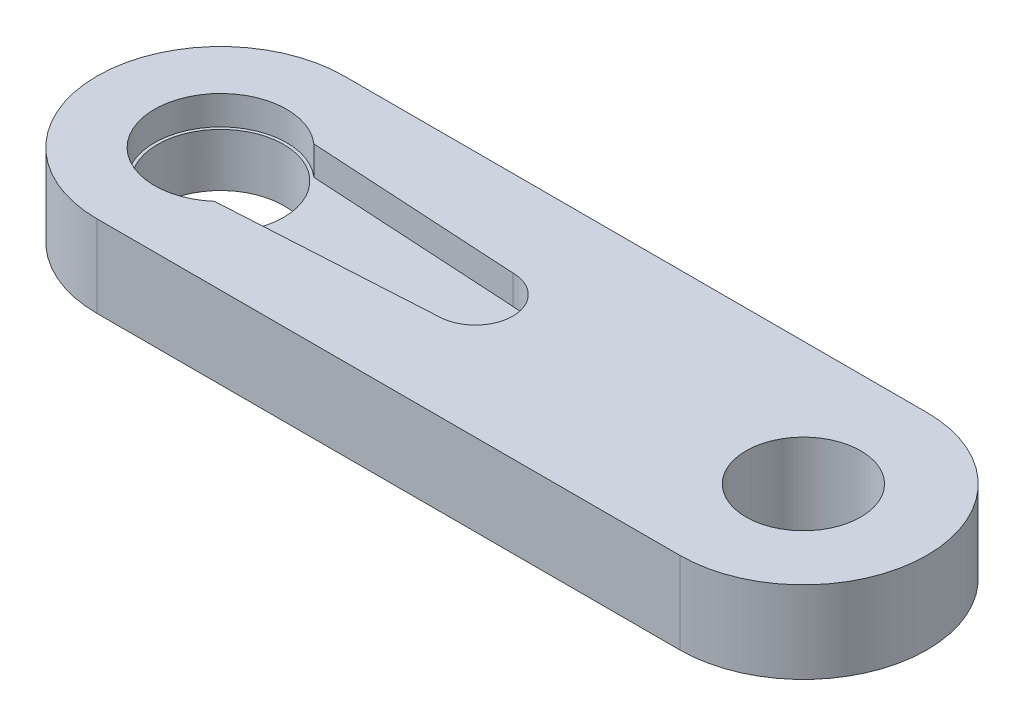
SolidWorks part; units mm, degrees
ref_plane "Front Plane" through (0, 0, 0) normal (0, 0, 1) x (1, 0, 0)
ref_plane "Top Plane" through (0, 0, 0) normal (0, 1, 0) x (1, 0, 0)
ref_plane "Right Plane" through (0, 0, 0) normal (1, 0, 0) x (0, 0, -1)
sketch "Sketch1" plane through (0, 0, 0) normal (0, 1, 0) x (1, 0, 0)
  line L0 (0, 0) -> (40, 0) construction
  line L1 (0, 7) -> (33, 7)
  line L2 (0, -7) -> (33, -7)
  arc A0 (0, 7) -> (0, -7) centre (0, 0) ccw
  arc A2 (33, -7) -> (33, 7) centre (33, 0) ccw
  point P5 (40, 0)
  point P9 (0, 0)
  point P10 (0, 0)
  point P11 (40, 0)
  dimension "D1" = 7
  dimension "D2" = 40
extrude "Boss-Extrude1" add sketch "Sketch1" along normal blind 3
sketch "Sketch2" plane through (0, 0, 0) normal (0, -1, 0) x (1, 0, 0)
  circle A0 centre (0, 0) radius 3.575
  dimension "D1" = 7.15
extrude "Cut-Extrude1" cut sketch "Sketch2" against normal blind 3.95
sketch "Sketch3" plane through (0, 3, 0) normal (0, 1, 0) x (1, 0, 0)
  line L0 (2.3996, 2.65) -> (2.3996, -2.65) construction
  line L1 (3.575, 0) -> (16.375, 0) construction
  line L2 (2.3996, -2.65) -> (14.425, -1.95) construction
  line L3 (14.425, -1.95) -> (14.425, 1.95) construction
  line L4 (14.425, 1.95) -> (2.3996, 2.65) construction
  line L5 (14.43, 2.12) -> (2.4685, 2.8163)
  line L6 (2.4685, -2.8163) -> (14.43, -2.12)
  line L11 (0, -7) -> (33, -7)
  line L12 (33, 7) -> (0, 7)
  line L13 (0, -7) -> (33, -7)
  line L14 (33, 7) -> (0, 7)
  arc A1 (14.425, -1.95) -> (14.425, 1.95) centre (14.425, 0) ccw construction
  circle A2 centre (0, 0) radius 3.575 construction
  circle A3 centre (14.425, 0) radius 1.95 construction
  circle A4 centre (0, 0) radius 3.575 construction
  arc A5 (2.3996, -2.65) -> (2.3996, 2.65) centre (0, 0) cw construction
  arc A7 (2.4685, -2.8163) -> (2.4685, 2.8163) centre (0, 0) cw
  arc A8 (14.43, -2.12) -> (14.43, 2.12) centre (14.425, 0) ccw
  arc A10 (33, -7) -> (33, 7) centre (33, 0) ccw
  arc A12 (0, 7) -> (0, -7) centre (0, 0) ccw
  arc A14 (0, 7) -> (0, -7) centre (0, 0) ccw
  arc A17 (33, -7) -> (33, 7) centre (33, 0) ccw
  arc A18 (33, -7) -> (33, 7) centre (33, 0) ccw
  point P0 (33, 0)
  point P3 (0, 0)
  point P4 (2.3996, 0)
  dimension "D5" = 0
  dimension "D3" = 3.9
  dimension "D6" = 0
  dimension "D1" = 5.3
  dimension "D2" = 12.8
  dimension "D4" = 0.17
extrude "Boss-Extrude2" add sketch "Sketch3" along normal blind 1.64
sketch "Sketch4" plane through (0, 4.64, 0) normal (0, 1, 0) x (1, 0, 0)
  circle A0 centre (33, 0) radius 3.25
  arc A2 (14.43, -2.12) -> (14.43, 2.12) centre (14.425, 0) ccw construction
  point P2 (32.6158, 0)
  point P3 (33, 0)
  point P7 (16.545, 0)
  dimension "D1" = 6.5
extrude "Cut-Extrude2" cut sketch "Sketch4" against normal up to surface (4.64 mm away) up to face at (0, 0, -3.575)
